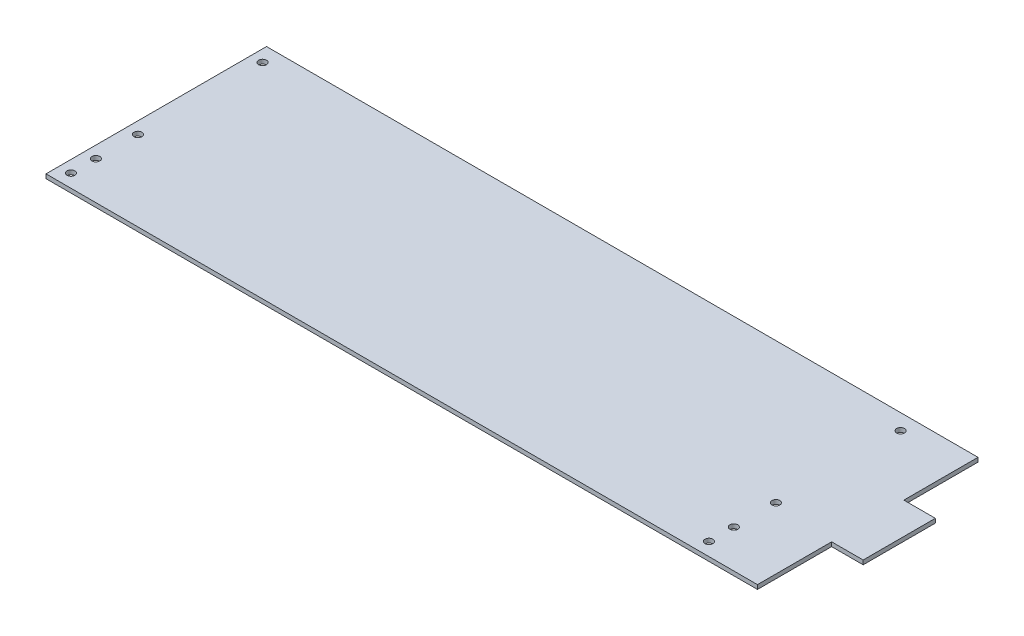
SolidWorks part; units mm, degrees
ref_plane "Front Plane" through (0, 0, 0) normal (0, 0, 1) x (1, 0, 0)
ref_plane "Top Plane" through (0, 0, 0) normal (0, 1, 0) x (1, 0, 0)
ref_plane "Right Plane" through (0, 0, 0) normal (1, 0, 0) x (0, 0, -1)
sketch "Sketch1" plane through (0, 0, 0) normal (0, 1, 0) x (1, 0, 0)
  line L0 (252, 42) -> (283, 42)
  line L1 (0, 0) -> (252, 0)
  line L2 (0, 0) -> (0, 84)
  line L3 (0, 84) -> (252, 84)
  line L4 (252, 0) -> (252, 84)
  line L5 (271, 84) -> (271, 0)
  line L6 (271, 0) -> (252, 0)
  line L7 (271, 84) -> (252, 84)
  line L8 (283, 55.75) -> (283, 28.25)
  line L9 (283, 28.25) -> (271, 28.25)
  line L10 (283, 55.75) -> (271, 55.75)
  line L11 (126, 84) -> (126, 0) construction
  circle A0 centre (4.5, 78) radius 1.5
  circle A1 centre (4.5, 5) radius 1.5
  circle A2 centre (247.5, 5) radius 1.5
  circle A3 centre (247.5, 78) radius 1.5
  circle A4 centre (4.5, 14.5) radius 1.5
  circle A5 centre (4.5, 30.5) radius 1.5
  circle A6 centre (247.5, 14.5) radius 1.5
  circle A7 centre (247.5, 30.5) radius 1.5
  point P10 (271, 42)
  point P14 (283, 42)
  point P29 (0, 0)
  dimension "D6" = 4.5
  dimension "D8" = 73
  dimension "D9" = 3
  dimension "D10" = 9.5
  dimension "D1" = 84
  dimension "D2" = 252
  dimension "D3" = 31
  dimension "D4" = 19
  dimension "D5" = 27.5
  dimension "D7" = 6
  dimension "D11" = 16
extrude "Boss-Extrude1" add sketch "Sketch1" along normal blind 1.6 contours L1 L4 L3 L2 | L5 L7 L4 L0 | L6 L5 L0 L4 | L9 L8 L0 L5 | L8 L10 L5 L0 | L11 L3 L2 L1 A1 A0
